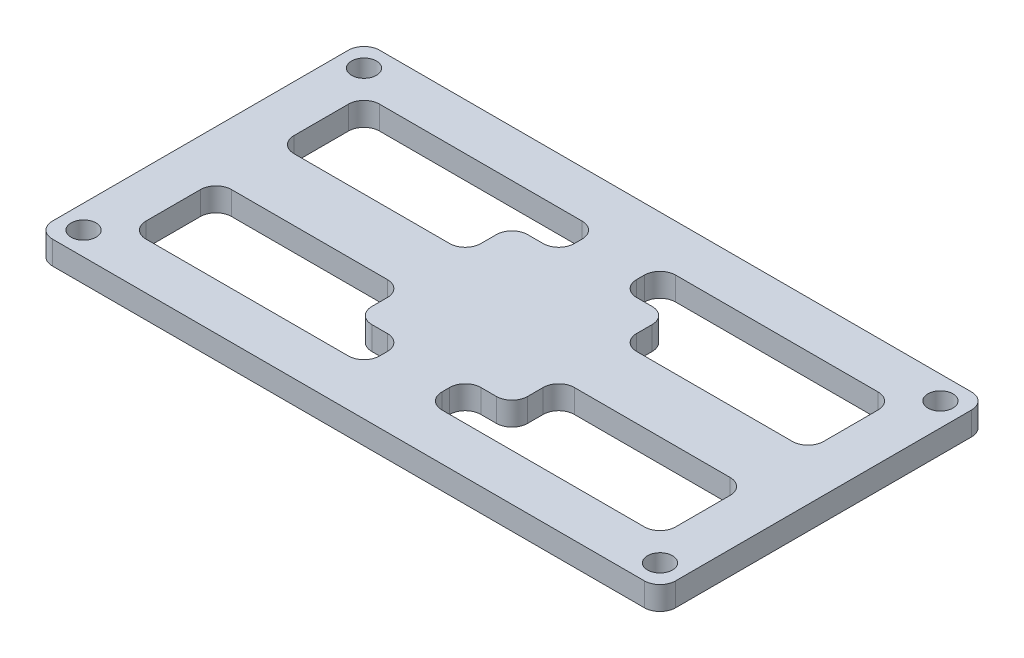
SolidWorks part; units mm, degrees
material "Thornel Mat VMA"
ref_plane "前视基准面" through (0, 0, 0) normal (0, 0, 1) x (1, 0, 0)
ref_plane "上视基准面" through (0, 0, 0) normal (0, 1, 0) x (1, 0, 0)
ref_plane "右视基准面" through (0, 0, 0) normal (1, 0, 0) x (0, 0, -1)
other "Configuration Table"
sketch "草图1" plane through (0, 0, 0) normal (0, 1, 0) x (1, 0, 0)
  line L1 (37, -18) -> (-37, -18) construction
  line L2 (37, -18) -> (37, 18) construction
  line L3 (37, 18) -> (-37, 18) construction
  line L4 (-37, -18) -> (-37, 18) construction
  line L5 (37, -18) -> (-37, 18) construction
  line L6 (37, 18) -> (-37, -18) construction
  line L7 (40, -21) -> (-40, -21)
  line L8 (40, -21) -> (40, 21)
  line L9 (40, 21) -> (-40, 21)
  line L10 (-40, -21) -> (-40, 21)
  line L11 (40, -21) -> (-40, 21) construction
  line L12 (40, 21) -> (-40, -21) construction
  line L13 (10, -10) -> (-10, -10)
  line L14 (10, -10) -> (10, 10)
  line L15 (10, 10) -> (-10, 10)
  line L16 (-10, -10) -> (-10, 10)
  line L17 (10, -10) -> (-10, 10) construction
  line L18 (10, 10) -> (-10, -10) construction
  line L19 (34, -15) -> (-34, -15)
  line L20 (34, -15) -> (34, 15)
  line L21 (34, 15) -> (-34, 15)
  line L22 (-34, -15) -> (-34, 15)
  line L23 (34, -15) -> (-34, 15) construction
  line L24 (34, 15) -> (-34, -15) construction
  line L25 (4, -15) -> (-4, -15)
  line L26 (4, -15) -> (4, 15)
  line L27 (4, 15) -> (-4, 15)
  line L28 (-4, -15) -> (-4, 15)
  line L29 (4, -15) -> (-4, 15) construction
  line L30 (4, 15) -> (-4, -15) construction
  line L31 (34, -4) -> (-34, -4)
  line L32 (34, -4) -> (34, 4)
  line L33 (34, 4) -> (-34, 4)
  line L34 (-34, -4) -> (-34, 4)
  line L35 (34, -4) -> (-34, 4) construction
  line L36 (34, 4) -> (-34, -4) construction
  circle A0 centre (-37, 18) radius 1.6
  circle A1 centre (37, 18) radius 1.6
  circle A2 centre (37, -18) radius 1.6
  circle A3 centre (-37, -18) radius 1.6
  point P0 (0, 0)
  point P10 (0, 0)
  point P15 (0, 0)
  point P20 (0, 0)
  point P25 (0, 0)
  point P30 (0, 0)
  dimension "D3" = 3.2
  dimension "D1" = 74
  dimension "D2" = 36
  dimension "D4" = 3
  dimension "D5" = 3
  dimension "D6" = 20
  dimension "D7" = 20
  dimension "D8" = 6
  dimension "D9" = 6
  dimension "D10" = 8
  dimension "D11" = 8
extrude "凸台-拉伸1" add sketch "草图1" along normal blind 3 contours L10 L7 L8 L9 A3 A2 A1 A0 L19 L22 L21 L20 | L28 L15 L26 L21 | L13 L28 L15 L16 | L28 L13 L26 L15 | L26 L13 L14 L15 | L28 L19 L26 L13 | L33 L26 L15 L28 | L33 L28 L15 L16 | L28 L31 L16 L13 | L26 L31 L28 L13 | L14 L31 L26 L13 | L33 L14 L15 L26 | L16 L33 L22 L31 | L20 L33 L14 L31
fillet "圆角1" radius 2 24 edges at (34, 1.5, 15) (34, 1.5, 4) (10, 1.5, 4) (10, 1.5, 10) (4, 1.5, 10) (4, 1.5, 15) (-4, 1.5, 10) (-10, 1.5, 10) (-10, 1.5, 4) (-34, 1.5, 4) (-34, 1.5, 15) (-4, 1.5, 15) (-4, 1.5, -15) (-34, 1.5, -15) (-34, 1.5, -4) (-10, 1.5, -4) (-10, 1.5, -10) (-4, 1.5, -10) (34, 1.5, -4) (34, 1.5, -15) (4, 1.5, -15) (4, 1.5, -10) (10, 1.5, -10) (10, 1.5, -4)
fillet "圆角2" radius 2 4 edges at (40, 1.5, -21) (40, 1.5, 21) (-40, 1.5, 21) (-40, 1.5, -21)
